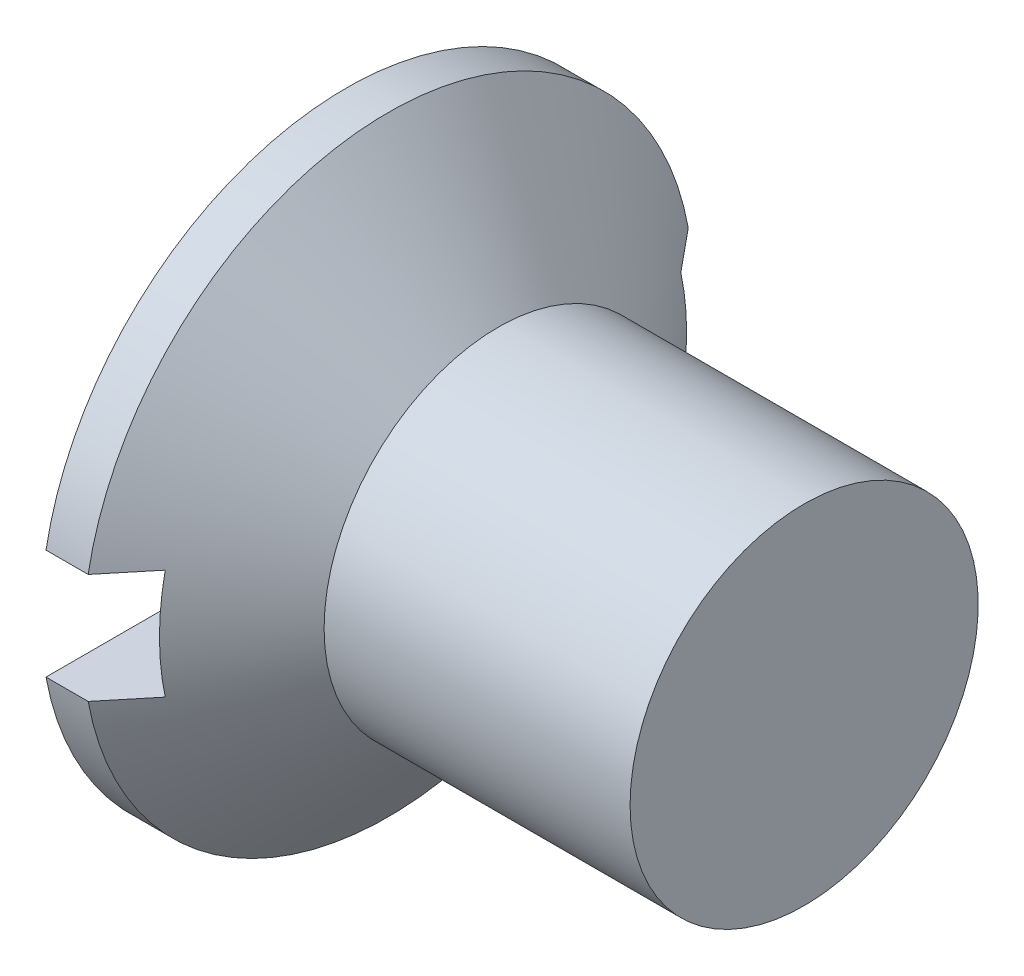
SolidWorks part; units mm, degrees
revolve "Base-Revolve" add sketch "BodySke" angle 360 about L5
sketch "BodySke" plane through (0, 0, 0) normal (0, 0, 1) x (1, 0, 0)
  line L0 (0, 0) -> (0, 4.2291)
  line L1 (0, 4.2291) -> (0.5843, 4.2291)
  line L2 (2.1082, 2.413) -> (6.35, 2.413)
  line L3 (6.35, 2.413) -> (6.35, 0)
  line L4 (6.35, 0) -> (0, 0)
  line L5 (-6.35, 0) -> (82.55, 0) construction
  line L6 (2.1082, -2.413) -> (6.35, -2.413) construction
  line L7 (0.5843, -4.2291) -> (2.1082, -2.413) construction
  line L8 (0.5843, 4.2291) -> (2.1082, 2.413)
  line L9 (0, -4.2291) -> (0.5843, -4.2291) construction
  line L10 (3.1674, 4.0005) -> (3.1674, -5.5245) construction
  line L11 (0, 6.35) -> (0, -3.175) construction
  dimension "Diameter" = 4.826
  dimension "Length" = 6.35
  dimension "Head_ht" = 2.1082
  dimension "Head_dia" = 8.4582
  dimension "Head_ang" = 100
  dimension "D6" = 0.5843
  dimension "Advance" = 1.0592
  dimension "Thread_nom" = 6.35
cosmetic thread "ThreadCosmetic" [suppressed] parameters "Thread_length"=3.1826, "Thread_minor"=3.5662
extrude "Slot" cut sketch "Sketch2" against normal blind 1.0668
sketch "Sketch2" plane through (0, 0, 0) normal (-1, 0, 0) x (0, 0, 1)
  line L0 (-4.2291, -0.762) -> (4.2291, -0.762)
  line L1 (-4.2291, -0.762) -> (-4.2291, 0.762)
  line L2 (4.2291, 0.762) -> (-4.2291, 0.762)
  line L3 (4.2291, 0.762) -> (4.2291, -0.762)
  dimension "Slot_width" = 1.524
  dimension "D1" = 0.762
  dimension "D2" = 8.4582
  dimension "D3" = 4.2291
ref_plane "Plane1" through (0, 0, 0) normal (0, 0, 1) x (1, 0, 0)
ref_plane "Plane2" through (0, 0, 0) normal (0, 1, 0) x (1, 0, 0)
ref_plane "Plane3" through (0, 0, 0) normal (1, 0, 0) x (0, 0, -1)
sketch "Sketch3" plane through (0, 0, 0) normal (-1, 0, 0) x (0, 0, 1)
  line L0 (-0.5334, 2.8575) -> (0.5334, 2.8575)
  line L1 (0.5334, 2.8575) -> (0.5334, -2.8575)
  line L2 (0.5334, -2.8575) -> (-0.5334, -2.8575)
  line L3 (-0.5334, -2.8575) -> (-0.5334, 2.8575)
  dimension "Cross_dia" = 5.715
  dimension "Cross_width" = 1.0668
  dimension "D1" = 2.8575
  dimension "D2" = 0.5334
ref_plane "Plane4" through (3.7338, 0, 0) normal (-1, 0, 0) x (0, 0, 1)
sketch "Sketch4" plane through (3.7338, 0, 0) normal (-1, 0, 0) x (0, 0, 1)
  line L0 (-0.2667, 0.2667) -> (0.2667, 0.2667)
  line L3 (0.2667, 0.2667) -> (0.2667, -0.2667)
  line L4 (0.2667, -0.2667) -> (-0.2667, -0.2667)
  line L5 (-0.2667, -0.2667) -> (-0.2667, 0.2667)
  dimension "D2" = 0.5334
  dimension "D1" = 0.5334
  dimension "D3" = 0.2667
  dimension "D4" = 0.2667
loft "Cross" cut profiles "Sketch3", "Sketch4"
pattern_circular "CirPattern1" count 2 every 90 about axis through (0, 0, 0) along (1, 0, 0) of "Cross"
sketch "ThdSchSke" plane through (0, 0, 0) normal (0, 0, 1) x (1, 0, 0)
  line L0 (3.1674, -1.7831) -> (2.7263, -2.413)
  line L1 (3.1674, -1.7831) -> (3.6085, -2.413)
  line L2 (3.6085, -2.413) -> (3.6085, -3.0162)
  line L3 (-3.175, 0) -> (5.1513, 0) construction
  line L5 (3.6085, -3.0162) -> (2.7263, -3.0162)
  line L6 (2.7263, -3.0162) -> (2.7263, -2.413)
  line L7 (0, 4.2291) -> (0, 0.762) construction
  dimension "Diameter" = 4.826
  dimension "Thread_minor" = 3.5662
  dimension "Start" = 3.1674
revolve "ThreadSchematic" [suppressed] cut sketch "ThdSchSke" angle 360 about L3
pattern_linear "ThdSchPat" [suppressed]
equation "\"D1@Sketch3\" = \"Cross_dia@Sketch3\" / 2"
equation "\"D2@Sketch3\" = \"Cross_width@Sketch3\" / 2"
equation "\"D1@Sketch4\" = \"Cross_width@Sketch3\" *.5"
equation "\"D2@Sketch4\" = \"D1@Sketch4\""
equation "\"D4@Sketch4\" = \"D2@Sketch4\" / 2"
equation "\"D3@Sketch4\" = \"D1@Sketch4\" / 2"
equation "\"D1@Sketch2\" = \"Slot_width@Sketch2\" / 2"
equation "\"D2@Sketch2\" = \"Head_dia@BodySke\""
equation "\"D3@Sketch2\" = \"D2@Sketch2\" / 2"
equation "\"Thread_length@ThreadCosmetic\" = ((sgn( (\"Length@BodySke\" - \"Advance@BodySke\" - \"Head_ht@BodySke\" ) - \"Thread_nom@BodySke\" )-1)*( (\"Length@BodySke\" - \"Advance@BodySke\" - \"Head_ht@BodySke\" ) - \"Thread_nom@BodySke\" ))/-2+ \"Thread_nom@BodySke\""
equation "\"Thread_minor@ThdSchSke\" = \"Thread_minor@ThreadCosmetic\""
equation "\"Diameter@ThdSchSke\" = \"Diameter@BodySke\""
equation "\"Overcut@ThdSchSke\" = \"Diameter@BodySke\" * 1.25"
equation "\"Start@ThdSchSke\" = 0.000001 + \"Length@BodySke\" - \"Thread_length@ThreadCosmetic\"  '---Countersunk---"
equation "\"Num_threads@ThdSchPat\" = int( \"Thread_length@ThreadCosmetic\" / \"Advance@BodySke\" + 0.999 )  + 1"
equation "\"Advance@ThdSchPat\" = \"Thread_length@ThreadCosmetic\" /  (\"Num_threads@ThdSchPat\" - 1) 'relax it"
